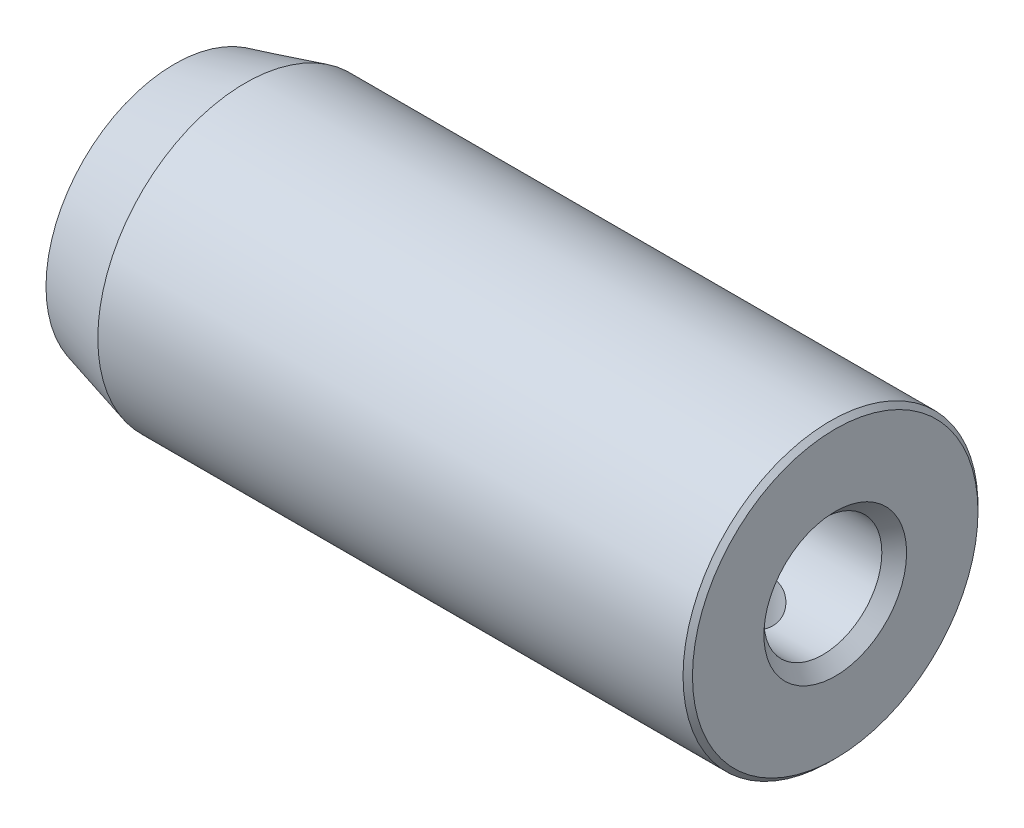
SolidWorks part; units mm, degrees
material "AISI 1020"
ref_plane "Plano superior" through (0, 0, 0) normal (0, 0, 1) x (1, 0, 0)
ref_plane "Plano frontal" through (0, 0, 0) normal (0, 1, 0) x (1, 0, 0)
ref_plane "Plano direito" through (0, 0, 0) normal (1, 0, 0) x (0, 0, -1)
sketch "Esboço1" plane through (0, 0, 0) normal (0, 1, 0) x (1, 0, 0)
  line L0 (0, 0) -> (27.9411, 0) construction
  line L1 (-0.0589, 6.25) -> (27.9411, 6.25)
  line L2 (27.9411, 6.25) -> (27.9411, 0)
  line L3 (27.9411, 0) -> (19.9411, 0)
  line L4 (19.9411, 0) -> (19.9411, 5)
  line L5 (19.9411, 5) -> (-0.0589, 5)
  line L6 (-0.0589, 5) -> (-0.0589, 6.25)
  dimension "D1" = 28
  dimension "D2" = 6.25
  dimension "D3" = 8
  dimension "D4" = 0
  dimension "D5" = 5
revolve "Revolução1" add sketch "Esboço1" angle 360 about L0
sketch "Esboço2" plane through (27.9411, 0, 0) normal (1, 0, 0) x (0, 0, -1)
  point P0 (0, 0)
hole_wizard "Furo roscado de M61" positions "Esboço5" profile "Esboço6" tap size "M6" standard "DIN" end condition up to next
sketch "Esboço5" plane through (27.9411, 0, 0) normal (1, 0, 0) x (0, 0, -1)
  point P0 (0, 0)
sketch "Esboço6" plane through (27.9411, 0, 0) normal (0, 1, 0) x (0, 0, -1)
  line L0 (0, 0) -> (0, 8)
  line L1 (0, 8) -> (2.5, 8)
  line L2 (2.5, 8) -> (2.5, 0.525)
  line L3 (2.5, 0.525) -> (3.025, 0)
  line L5 (3.025, 0) -> (0, 0)
  line L6 (-2.5, 0.525) -> (-3.025, 0) construction
  line L11 (0, -6.35) -> (0, 107.95) construction
  dimension "Thru Tap Drill Dia." = 5
  dimension "Thru Tap Drill Depth" = 8
  dimension "Near C'Sink Dia." = 6.05
  dimension "Near C'Sink Angle" = 90
cosmetic thread "Rosca de furo1" parameters "D2"=6
cosmetic thread "Representação de rosca1" parameters "D2"=5.838
chamfer "Chanfro1" distance 0.2 angle 45 1 edges at (27.9411, 0, 6.25)
chamfer "Chanfro3" distance 3 angle 15 1 edges at (-0.0589, 0, 6.25)
sketch "Esboço7" plane through (0, 0, 0) normal (0, 1, 0) x (1, 0, 0)
  circle A0 centre (23.9411, 0) radius 1.35
  dimension "D1" = 2.7
extrude "Corte-extrusão1" cut sketch "Esboço7" against normal up to next
